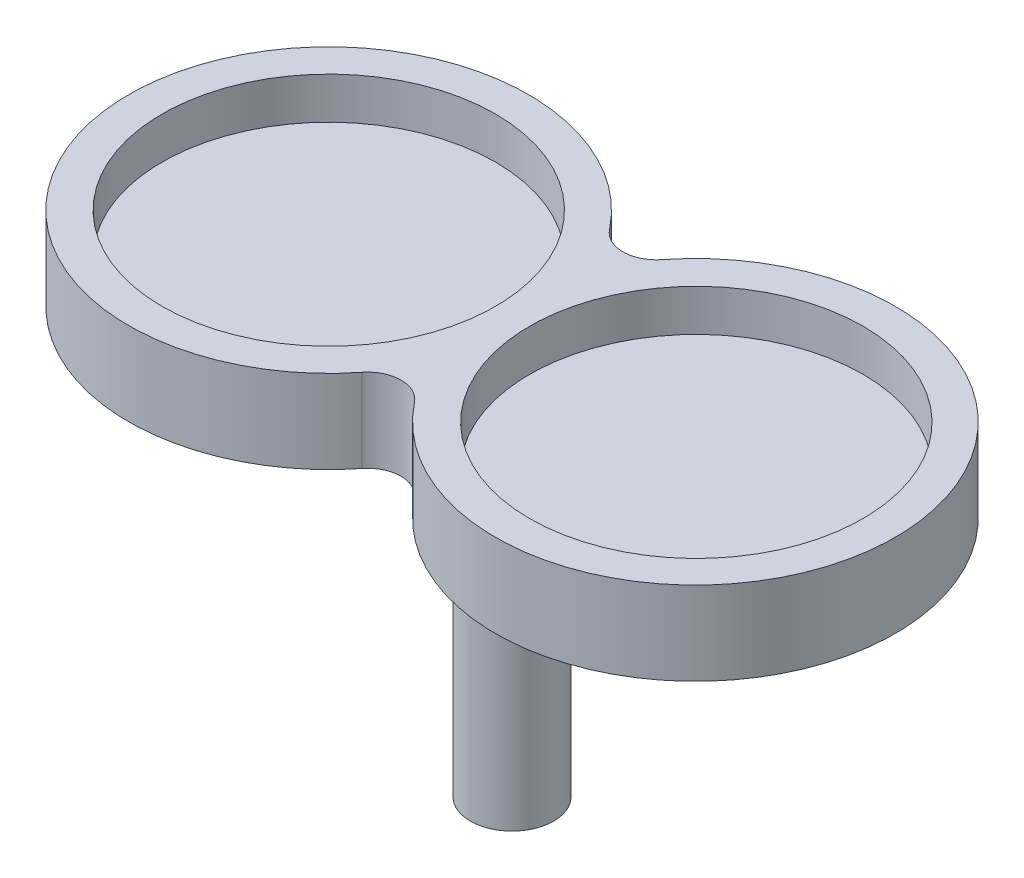
SolidWorks part; units mm, degrees
ref_plane "Front Plane" through (0, 0, 0) normal (0, 0, 1) x (1, 0, 0)
ref_plane "Top Plane" through (0, 0, 0) normal (0, 1, 0) x (1, 0, 0)
ref_plane "Right Plane" through (0, 0, 0) normal (1, 0, 0) x (0, 0, -1)
sketch "Sketch2" plane through (0, 0, 0) normal (0, 1, 0) x (1, 0, 0)
  arc A0 (0, -6.0907) -> (0, 6.0907) centre (13.97, 0) ccw
  arc A1 (0, 6.0907) -> (0, -6.0907) centre (-13.97, 0) ccw
  dimension "D2" = 27.94
extrude "Boss-Extrude1" add sketch "Sketch2" along normal blind 6.35 contours A1 A0
sketch "Sketch3" plane through (0, 6.35, 0) normal (0, 1, 0) x (1, 0, 0)
  circle A0 centre (13.97, 0) radius 12.7
  circle A1 centre (-13.9597, 0) radius 12.7
  point P5 (-13.9597, 0)
extrude "Cut-Extrude1" cut sketch "Sketch3" against normal blind 3.175 contours A1
sketch "Sketch5" plane through (0, 6.35, 0) normal (0, 1, 0) x (1, 0, 0)
  circle A0 centre (14.0456, 0) radius 12.7
  point P2 (14.0456, 0)
extrude "Cut-Extrude2" cut sketch "Sketch5" against normal blind 3.175
sketch "Sketch6" plane through (0, 0, 0) normal (0, -1, 0) x (-1, 0, 0)
  circle A2 centre (0, 0) radius 3.175
extrude "Boss-Extrude2" add sketch "Sketch6" along normal blind 25.4
fillet "Fillet1" radius 2.54 3 edges at (0, 3.175, -6.0907) (0, 3.175, 6.0907) (0, 0, 3.175)
